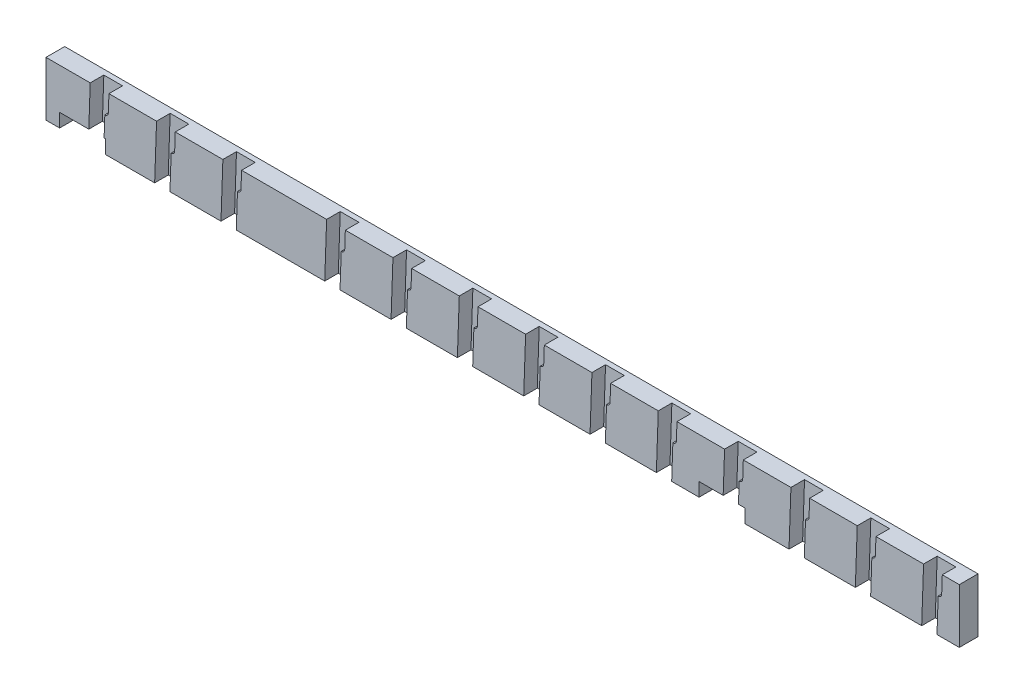
SolidWorks part; units mm, degrees
ref_plane "Front Plane" through (0, 0, 0) normal (0, 0, 1) x (1, 0, 0)
ref_plane "Top Plane" through (0, 0, 0) normal (0, 1, 0) x (1, 0, 0)
ref_plane "Right Plane" through (0, 0, 0) normal (1, 0, 0) x (0, 0, -1)
sketch "Sketch1" plane through (0, 0, 0) normal (0, 0, 1) x (1, 0, 0)
  line L1 (852.4875, 50.8) -> (-852.4875, 50.8)
  line L2 (852.4875, 50.8) -> (852.4875, -50.8)
  line L3 (852.4875, -50.8) -> (-852.4875, -50.8)
  line L4 (-852.4875, 50.8) -> (-852.4875, -50.8)
  line L5 (852.4875, 50.8) -> (-852.4875, -50.8) construction
  line L6 (852.4875, -50.8) -> (-852.4875, 50.8) construction
  point P0 (0, 0)
  dimension "D1" = 1704.975
  dimension "D2" = 101.6
extrude "Boss-Extrude1" add sketch "Sketch1" along normal blind 34.925
sketch "Sketch2" plane through (0, 0, 34.925) normal (0, 0, 1) x (1, 0, 0)
  line L0 (782.2645, -50.8) -> (785.8125, 50.8)
  line L1 (852.4875, 50.8) -> (-852.4875, 50.8) construction
  line L2 (-852.4875, -50.8) -> (852.4875, -50.8) construction
  line L3 (782.2645, -50.8) -> (810.8395, -50.8)
  line L4 (810.8395, -50.8) -> (813.057, 12.7)
  line L5 (813.057, 12.7) -> (813.2749, 12.7)
  line L6 (819.621, 18.8284) -> (820.7375, 50.8)
  line L7 (820.7375, 50.8) -> (785.8125, 50.8)
  line L8 (658.4395, -50.8) -> (661.9875, 50.8)
  line L9 (658.4395, -50.8) -> (687.0145, -50.8)
  line L10 (687.0145, -50.8) -> (689.232, 12.7)
  line L11 (689.232, 12.7) -> (689.4499, 12.7)
  line L12 (695.796, 18.8284) -> (696.9125, 50.8)
  line L13 (696.9125, 50.8) -> (661.9875, 50.8)
  line L14 (534.6145, -50.8) -> (538.1625, 50.8)
  line L15 (534.6145, -50.8) -> (563.1895, -50.8)
  line L16 (563.1895, -50.8) -> (565.407, 12.7)
  line L17 (565.407, 12.7) -> (565.6249, 12.7)
  line L18 (571.971, 18.8284) -> (573.0875, 50.8)
  line L19 (573.0875, 50.8) -> (538.1625, 50.8)
  line L20 (410.7895, -50.8) -> (414.3375, 50.8)
  line L21 (410.7895, -50.8) -> (439.3645, -50.8)
  line L22 (439.3645, -50.8) -> (441.582, 12.7)
  line L23 (441.582, 12.7) -> (441.7999, 12.7)
  line L24 (448.146, 18.8284) -> (449.2625, 50.8)
  line L25 (449.2625, 50.8) -> (414.3375, 50.8)
  line L26 (286.9645, -50.8) -> (290.5125, 50.8)
  line L27 (286.9645, -50.8) -> (315.5395, -50.8)
  line L28 (315.5395, -50.8) -> (317.757, 12.7)
  line L29 (317.757, 12.7) -> (317.9749, 12.7)
  line L30 (324.321, 18.8284) -> (325.4375, 50.8)
  line L31 (325.4375, 50.8) -> (290.5125, 50.8)
  line L32 (163.1395, -50.8) -> (166.6875, 50.8)
  line L33 (163.1395, -50.8) -> (191.7145, -50.8)
  line L34 (191.7145, -50.8) -> (193.932, 12.7)
  line L35 (193.932, 12.7) -> (194.1499, 12.7)
  line L36 (200.496, 18.8284) -> (201.6125, 50.8)
  line L37 (201.6125, 50.8) -> (166.6875, 50.8)
  line L38 (39.3145, -50.8) -> (42.8625, 50.8)
  line L39 (39.3145, -50.8) -> (67.8895, -50.8)
  line L40 (67.8895, -50.8) -> (70.107, 12.7)
  line L41 (70.107, 12.7) -> (70.3249, 12.7)
  line L42 (76.671, 18.8284) -> (77.7875, 50.8)
  line L43 (77.7875, 50.8) -> (42.8625, 50.8)
  line L44 (-84.5105, -50.8) -> (-80.9625, 50.8)
  line L45 (-84.5105, -50.8) -> (-55.9355, -50.8)
  line L46 (-55.9355, -50.8) -> (-53.718, 12.7)
  line L47 (-53.718, 12.7) -> (-53.5001, 12.7)
  line L48 (-47.154, 18.8284) -> (-46.0375, 50.8)
  line L49 (-46.0375, 50.8) -> (-80.9625, 50.8)
  line L50 (-208.3355, -50.8) -> (-204.7875, 50.8)
  line L51 (-208.3355, -50.8) -> (-179.7605, -50.8)
  line L52 (-179.7605, -50.8) -> (-177.543, 12.7)
  line L53 (-177.543, 12.7) -> (-177.3251, 12.7)
  line L54 (-170.979, 18.8284) -> (-169.8625, 50.8)
  line L55 (-169.8625, 50.8) -> (-204.7875, 50.8)
  line L56 (-332.1605, -50.8) -> (-328.6125, 50.8)
  line L57 (-332.1605, -50.8) -> (-303.5855, -50.8)
  line L58 (-303.5855, -50.8) -> (-301.368, 12.7)
  line L59 (-301.368, 12.7) -> (-301.1501, 12.7)
  line L60 (-294.804, 18.8284) -> (-293.6875, 50.8)
  line L61 (-293.6875, 50.8) -> (-328.6125, 50.8)
  line L62 (-852.4875, 50.8) -> (-852.4875, -50.8) construction
  line L63 (-525.8355, -50.8) -> (-522.2875, 50.8)
  line L64 (-525.8355, -50.8) -> (-497.2605, -50.8)
  line L65 (-497.2605, -50.8) -> (-495.043, 12.7)
  line L66 (-495.043, 12.7) -> (-494.8251, 12.7)
  line L67 (-488.479, 18.8284) -> (-487.3625, 50.8)
  line L68 (-487.3625, 50.8) -> (-522.2875, 50.8)
  line L69 (-649.6605, -50.8) -> (-646.1125, 50.8)
  line L70 (-649.6605, -50.8) -> (-621.0855, -50.8)
  line L71 (-621.0855, -50.8) -> (-618.868, 12.7)
  line L72 (-618.868, 12.7) -> (-618.6501, 12.7)
  line L73 (-612.304, 18.8284) -> (-611.1875, 50.8)
  line L74 (-611.1875, 50.8) -> (-646.1125, 50.8)
  line L75 (-773.4855, -50.8) -> (-769.9375, 50.8)
  line L76 (-773.4855, -50.8) -> (-744.9105, -50.8)
  line L77 (-744.9105, -50.8) -> (-742.693, 12.7)
  line L78 (-742.693, 12.7) -> (-742.4751, 12.7)
  line L79 (-736.129, 18.8284) -> (-735.0125, 50.8)
  line L80 (-735.0125, 50.8) -> (-769.9375, 50.8)
  arc A0 (813.2749, 12.7) -> (819.621, 18.8284) centre (813.2749, 19.05) ccw
  arc A1 (689.4499, 12.7) -> (695.796, 18.8284) centre (689.4499, 19.05) ccw
  arc A2 (565.6249, 12.7) -> (571.971, 18.8284) centre (565.6249, 19.05) ccw
  arc A3 (441.7999, 12.7) -> (448.146, 18.8284) centre (441.7999, 19.05) ccw
  arc A4 (317.9749, 12.7) -> (324.321, 18.8284) centre (317.9749, 19.05) ccw
  arc A5 (194.1499, 12.7) -> (200.496, 18.8284) centre (194.1499, 19.05) ccw
  arc A6 (70.3249, 12.7) -> (76.671, 18.8284) centre (70.3249, 19.05) ccw
  arc A7 (-53.5001, 12.7) -> (-47.154, 18.8284) centre (-53.5001, 19.05) ccw
  arc A8 (-177.3251, 12.7) -> (-170.979, 18.8284) centre (-177.3251, 19.05) ccw
  arc A9 (-301.1501, 12.7) -> (-294.804, 18.8284) centre (-301.1501, 19.05) ccw
  arc A10 (-494.8251, 12.7) -> (-488.479, 18.8284) centre (-494.8251, 19.05) ccw
  arc A11 (-618.6501, 12.7) -> (-612.304, 18.8284) centre (-618.6501, 19.05) ccw
  arc A12 (-742.4751, 12.7) -> (-736.129, 18.8284) centre (-742.4751, 19.05) ccw
  dimension "D6" = 6.35
  dimension "D1" = 34.925
  dimension "D2" = 38.1
  dimension "D3" = 28.575
  dimension "D4" = 88
  dimension "D5" = 31.75
  dimension "D8" = 520.327
  dimension "D9" = 2
  dimension "D10" = 326.652
  dimension "D11" = 63.5
  dimension "D12" = 3
  dimension "D13" = 79.002
  dimension "D14" = 101.6
  dimension "D17" = 1704.975
  dimension "D29" = 1704.975
  dimension "D7" = 10
extrude "Cut-Extrude1" cut sketch "Sketch2" against normal blind 25.4
sketch "Sketch3" plane through (0, 0, 0) normal (0, 0, -1) x (-1, 0, 0)
  line L0 (852.4875, -50.8) -> (-852.4875, -50.8) construction
  line L1 (827.0875, -50.8) -> (741.3625, -50.8)
  line L2 (827.0875, -50.8) -> (827.0875, -25.4)
  line L3 (827.0875, -25.4) -> (741.3625, -25.4)
  line L4 (741.3625, -50.8) -> (741.3625, -25.4)
  line L5 (852.4875, 50.8) -> (852.4875, -50.8) construction
  line L6 (-366.7125, -25.4) -> (-452.4375, -25.4)
  line L7 (-452.4375, -25.4) -> (-452.4375, -50.8)
  line L8 (-452.4375, -50.8) -> (-366.7125, -50.8)
  line L9 (-366.7125, -50.8) -> (-366.7125, -25.4)
  dimension "D1" = 25.4
  dimension "D2" = 85.725
  dimension "D3" = 1108.075
  dimension "D4" = 85.725
  dimension "D5" = 25.4
  dimension "D6" = 25.4
extrude "Cut-Extrude2" cut sketch "Sketch3" against normal through all
